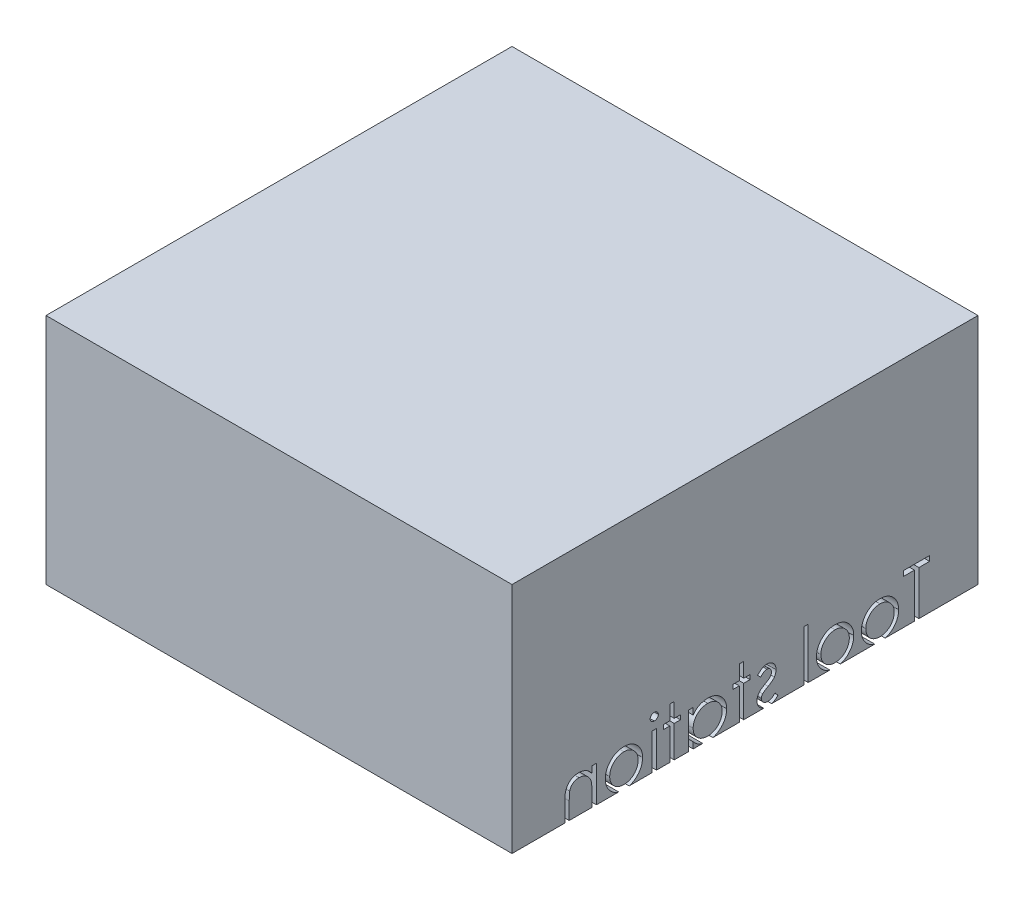
SolidWorks part; units mm, degrees
ref_plane "Front Plane" through (0, 0, 0) normal (0, 0, 1) x (1, 0, 0)
ref_plane "Top Plane" through (0, 0, 0) normal (0, 1, 0) x (1, 0, 0)
ref_plane "Right Plane" through (0, 0, 0) normal (1, 0, 0) x (0, 0, -1)
sketch "Sketch1" plane through (0, 0, 0) normal (1, 0, 0) x (0, 0, -1)
  line L1 (60, 30) -> (-60, 30)
  line L2 (60, 30) -> (60, -30)
  line L3 (60, -30) -> (-60, -30)
  line L4 (-60, 30) -> (-60, -30)
  line L5 (60, 30) -> (-60, -30) construction
  line L6 (60, -30) -> (-60, 30) construction
  point P0 (0, 0)
  dimension "D1" = 120
  dimension "D2" = 60
extrude "Boss-Extrude1" add sketch "Sketch1" along normal blind 120
sketch "Sketch2" plane through (0, 0, 0) normal (-1, 0, 0) x (0, 0, 1)
  text T0 "Tool station" font "Century Gothic" height in points 48
extrude "Cut-Extrude1" cut sketch "Sketch2" against normal blind 120
